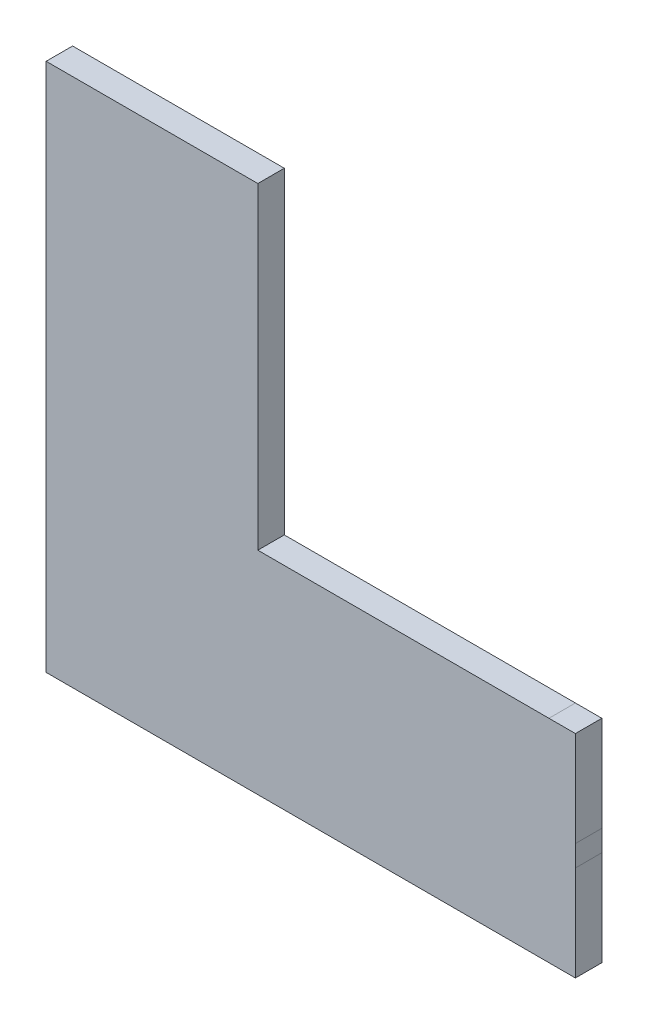
SolidWorks part; units mm, degrees
ref_plane "Front Plane" through (0, 0, 0) normal (0, 0, 1) x (1, 0, 0)
ref_plane "Top Plane" through (0, 0, 0) normal (0, 1, 0) x (1, 0, 0)
ref_plane "Right Plane" through (0, 0, 0) normal (1, 0, 0) x (0, 0, -1)
sketch "Sketch1" plane through (0, 0, 0) normal (0, 0, 1) x (1, 0, 0)
  line L0 (0, 0) -> (100, 0)
  line L1 (100, 0) -> (100, 40)
  line L2 (100, 40) -> (40, 40)
  line L3 (40, 40) -> (40, 100)
  line L4 (40, 100) -> (0, 100)
  line L5 (0, 100) -> (0, 0)
  dimension "D1" = 100
  dimension "D2" = 100
  dimension "D3" = 40
  dimension "D4" = 40
extrude "Boss-Extrude1" add sketch "Sketch1" along normal blind 5
sketch "Sketch2" plane through (100, 0, 0) normal (1, 0, 0) x (0, 0, -1)
  line L0 (-5, 0) -> (-5, 40) construction
  line L1 (-5, 22) -> (0, 22)
  line L2 (-5, 22) -> (-5, 18)
  line L3 (-5, 18) -> (0, 18)
  line L4 (0, 22) -> (0, 18)
  line L5 (0, 0) -> (0, 40) construction
  line L6 (-5, 0) -> (0, 0) construction
  dimension "D1" = 4
  dimension "D2" = 18
split line "Split Line1"
sketch "Sketch3" plane through (0, 40, 0) normal (0, 1, 0) x (1, 0, 0)
  line L0 (95, 0) -> (95, -5)
  line L1 (100, 0) -> (40, 0) construction
  line L2 (100, -5) -> (40, -5) construction
  line L3 (100, -5) -> (100, 0) construction
  dimension "D1" = 5
split line "Split Line2"
